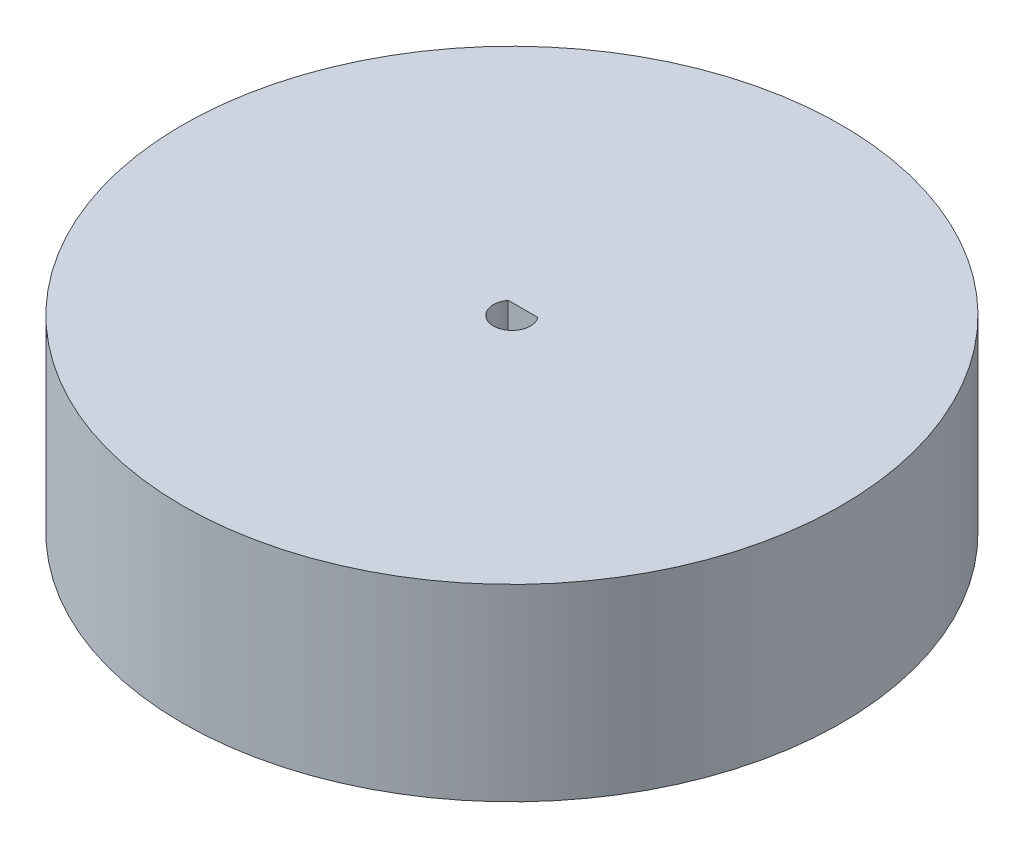
SolidWorks part; units mm, degrees
ref_plane "Front Plane" through (0, 0, 0) normal (0, 0, 1) x (1, 0, 0)
ref_plane "Top Plane" through (0, 0, 0) normal (0, 1, 0) x (1, 0, 0)
ref_plane "Right Plane" through (0, 0, 0) normal (1, 0, 0) x (0, 0, -1)
sketch "Sketch1" plane through (0, 0, 0) normal (0, 1, 0) x (1, 0, 0)
  line L0 (-1, 0.75) -> (1, 0.75)
  circle A1 centre (0, 0) radius 22.225
  circle A2 centre (0, 0) radius 1.25
  dimension "D1" = 2.5
  dimension "D2" = 44.45
  dimension "D3" = 2
extrude "Boss-Extrude1" add sketch "Sketch1" along normal blind 12.7
